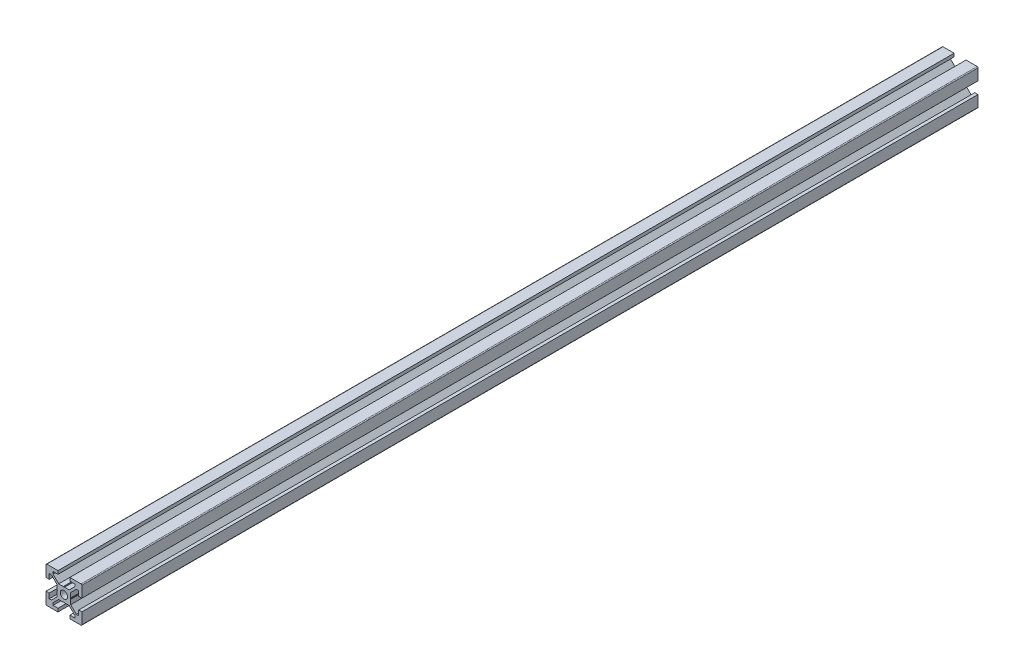
SolidWorks part; units mm, degrees
ref_plane "Front Plane" through (0, 0, 0) normal (0, 0, 1) x (1, 0, 0)
ref_plane "Top Plane" through (0, 0, 0) normal (0, 1, 0) x (1, 0, 0)
ref_plane "Right Plane" through (0, 0, 0) normal (1, 0, 0) x (0, 0, -1)
sketch "Sketch1" plane through (0, 0, 0) normal (0, 0, 1) x (1, 0, 0)
  line L0 (-3.3, 10) -> (-3.3, 8.2)
  line L1 (0, 0) -> (50000, 0) construction
  line L2 (-10, 3.3) -> (-10, 10)
  line L3 (-10, 10) -> (-3.3, 10)
  line L4 (0, 0) -> (0, 50000) construction
  line L5 (-10, -10) -> (10, 10) construction
  line L6 (-10, 10) -> (10, -10) construction
  line L7 (-2.9315, -3.78) -> (-0.34, -3.78)
  line L8 (-3.78, -2.9315) -> (-3.78, -0.34)
  line L9 (-2.9315, 3.78) -> (-0.34, 3.78)
  line L10 (3.78, -2.9315) -> (3.78, -0.34)
  line L11 (-3.78, -3.78) -> (3.78, 3.78) construction
  line L12 (-3.78, 3.78) -> (3.78, -3.78) construction
  line L13 (-6.08, 8.2) -> (-3.3, 8.2)
  line L14 (-8.2, 6.08) -> (-8.2, 3.3)
  line L15 (-8.2, 3.3) -> (-10, 3.3)
  line L16 (-8.2, 6.08) -> (-6.9285, 6.08)
  line L17 (-6.08, 8.2) -> (-6.08, 6.9285)
  line L18 (-6.9285, 6.08) -> (-3.78, 2.9315)
  line L19 (-6.08, 6.9285) -> (-2.9315, 3.78)
  line L20 (8.2, 6.08) -> (6.9285, 6.08)
  line L21 (8.2, 6.08) -> (8.2, 3.3)
  line L22 (8.2, 3.3) -> (10, 3.3)
  line L23 (10, 3.3) -> (10, 10)
  line L24 (10, 10) -> (3.3, 10)
  line L25 (3.3, 10) -> (3.3, 8.2)
  line L26 (6.08, 8.2) -> (3.3, 8.2)
  line L27 (6.08, 8.2) -> (6.08, 6.9285)
  line L28 (6.08, 6.9285) -> (2.9315, 3.78)
  line L29 (6.9285, 6.08) -> (3.78, 2.9315)
  line L30 (6.9285, -6.08) -> (3.78, -2.9315)
  line L31 (6.08, -6.9285) -> (2.9315, -3.78)
  line L32 (6.08, -8.2) -> (6.08, -6.9285)
  line L33 (6.08, -8.2) -> (3.3, -8.2)
  line L34 (3.3, -10) -> (3.3, -8.2)
  line L35 (10, -10) -> (3.3, -10)
  line L36 (10, -3.3) -> (10, -10)
  line L37 (8.2, -3.3) -> (10, -3.3)
  line L38 (8.2, -6.08) -> (8.2, -3.3)
  line L39 (8.2, -6.08) -> (6.9285, -6.08)
  line L40 (-6.08, -6.9285) -> (-2.9315, -3.78)
  line L41 (-6.9285, -6.08) -> (-3.78, -2.9315)
  line L42 (-6.08, -8.2) -> (-6.08, -6.9285)
  line L43 (-8.2, -6.08) -> (-6.9285, -6.08)
  line L44 (-8.2, -3.3) -> (-10, -3.3)
  line L45 (-8.2, -6.08) -> (-8.2, -3.3)
  line L46 (-6.08, -8.2) -> (-3.3, -8.2)
  line L47 (-10, -10) -> (-3.3, -10)
  line L48 (-10, -3.3) -> (-10, -10)
  line L49 (-3.3, -10) -> (-3.3, -8.2)
  line L50 (-0.34, 3.78) -> (0, 3.66)
  line L51 (0.34, 3.78) -> (0, 3.66)
  line L52 (0.34, 3.78) -> (2.9315, 3.78)
  line L53 (-3.78, -0.34) -> (-3.66, 0)
  line L54 (-3.78, 0.34) -> (-3.66, 0)
  line L55 (3.78, 0.34) -> (3.66, 0)
  line L56 (3.78, -0.34) -> (3.66, 0)
  line L57 (-0.34, -3.78) -> (0, -3.66)
  line L58 (0.34, -3.78) -> (0, -3.66)
  line L59 (3.78, 0.34) -> (3.78, 2.9315)
  line L60 (0.34, -3.78) -> (2.9315, -3.78)
  line L61 (-3.78, 0.34) -> (-3.78, 2.9315)
  circle A0 centre (0, 0) radius 2.05
  point P0 (0, 0)
  dimension "D3" = 4.1
  dimension "D1" = 20
  dimension "D2" = 20
  dimension "D4" = 7.56
  dimension "D5" = 6.7
  dimension "D6" = 6.7
  dimension "D7" = 0.6
  dimension "D8" = 3.92
  dimension "D9" = 0.34
  dimension "D10" = 0.12
extrude "Boss-Extrude1" add sketch "Sketch1" along normal blind 500
fillet "Fillet1" radius 0.5 4 edges at (-10, 10, 250) (-10, -10, 250) (10, -10, 250) (10, 10, 250)
